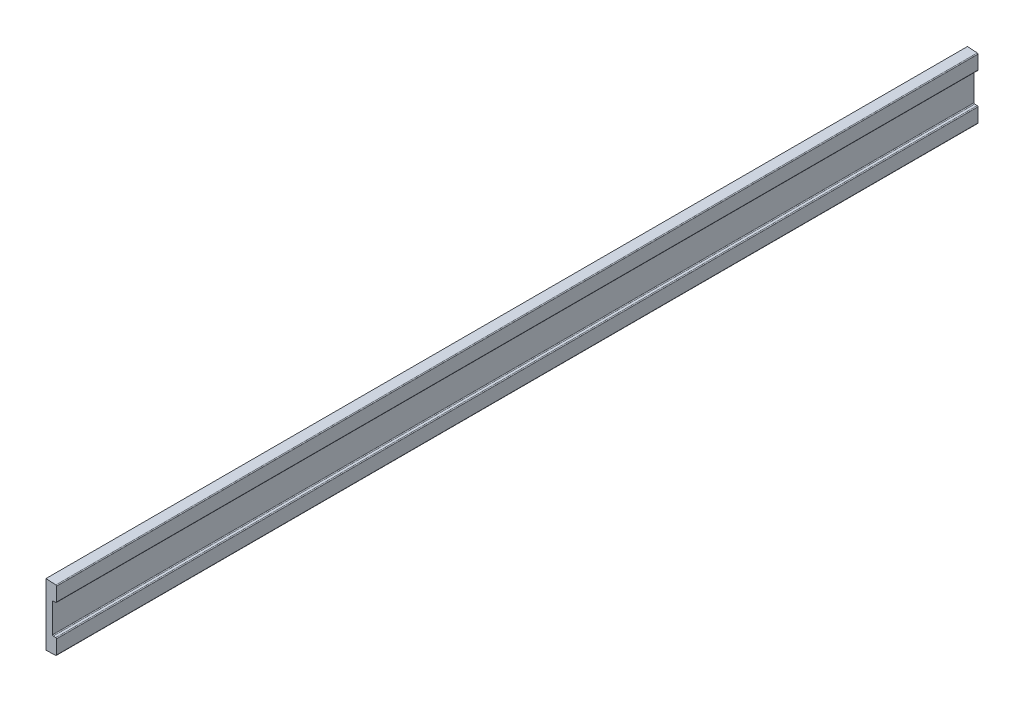
SolidWorks part; units mm, degrees
ref_plane "Front Plane" through (0, 0, 0) normal (0, 0, 1) x (1, 0, 0)
ref_plane "Top Plane" through (0, 0, 0) normal (0, 1, 0) x (1, 0, 0)
ref_plane "Right Plane" through (0, 0, 0) normal (1, 0, 0) x (0, 0, -1)
curve "Curve1"
  spline degree 3 poles (152.4, 0, 0) (152.2328, 0.0185, 0) (151.5718, 0.0917, 0) (150.114, 0.2839, 0) (147.7494, 0.6387, 0) (144.5559, 1.1702, 0) (140.6154, 1.8591, 0) (136.0078, 2.6715, 0) (130.8064, 3.5628, 0) (125.0738, 4.4862, 0) (118.8647, 5.3978, 0) (112.2333, 6.273, 0) (105.2435, 7.1061, 0) (97.9697, 7.8893, 0) (90.4927, 8.6067, 0) (82.8953, 9.2407, 0) (75.2587, 9.7775, 0) (67.6629, 10.1988, 0) (60.1868, 10.4917, 0) (52.9059, 10.6451, 0) (45.8917, 10.6446, 0) (39.2107, 10.4862, 0) (32.9233, 10.1644, 0) (27.0837, 9.6709, 0) (21.7372, 9.0165, 0) (16.9243, 8.2041, 0) (12.6763, 7.2498, 0) (9.0198, 6.1745, 0) (5.9657, 5.002, 0) (3.544, 3.7699, 0) (1.7048, 2.5315, 0) (0.5752, 1.3447, 0) (-0.1707, 0.2031, 0) (0.3376, -1.0018, 0) (1.7929, -1.5467, 0) (3.7942, -2.1772, 0) (6.6434, -2.6439, 0) (10.2161, -3.042, 0) (14.5301, -3.3199, 0) (19.534, -3.4977, 0) (25.1869, -3.5776, 0) (31.4286, -3.5738, 0) (38.1919, -3.4966, 0) (45.4016, -3.3493, 0) (52.9784, -3.1418, 0) (60.8387, -2.8853, 0) (68.895, -2.5879, 0) (77.0574, -2.2589, 0) (85.235, -1.9077, 0) (93.3354, -1.5502, 0) (101.266, -1.1955, 0) (108.9342, -0.8624, 0) (116.2465, -0.5575, 0) (123.1102, -0.3069, 0) (129.4317, -0.1079, 0) (135.1235, 0.028, 0) (140.1036, 0.1089, 0) (144.2994, 0.1399, 0) (147.6448, 0.1242, 0) (150.0834, 0.0865, 0) (151.3998, 0.0403, 0) (151.8986, 0.0229, 0) knots 0 0 0 0 0.001635 0.006466 0.014297 0.024884 0.037944 0.053194 0.070377 0.089257 0.109652 0.131396 0.154295 0.178097 0.202531 0.227329 0.252226 0.276966 0.301297 0.324972 0.347773 0.369494 0.389947 0.408979 0.426466 0.442307 0.456421 0.468774 0.479345 0.488156 0.495223 0.500608 0.504417 0.507344 0.511893 0.518766 0.528062 0.53975 0.553782 0.570059 0.588441 0.608748 0.63075 0.654208 0.678865 0.704451 0.730678 0.757254 0.783883 0.810266 0.836095 0.861073 0.884897 0.907258 0.927856 0.946395 0.962618 0.976286 0.987193 0.995147 1 1 1 1
sketch "Sketch1" plane through (0, 0, 0) normal (0, 0, 1) x (1, 0, 0)
  line L0 (151.8986, 0.0229) -> (152.4, 0)
  line L2 (0, 0) -> (0, 1.9929) construction
  spline S0 degree 3 poles (-13.6531, -1992.4593) (197.8364, 10.3076) (173.4363, -2.7909) (150.114, 0.2839) (147.7494, 0.6387) (144.5559, 1.1702) (140.6154, 1.8591) (136.0078, 2.6715) (130.8064, 3.5628) (125.0738, 4.4862) (118.8647, 5.3978) (112.2333, 6.273) (105.2435, 7.1061) (97.9697, 7.8893) (90.4927, 8.6067) (82.8953, 9.2407) (75.2587, 9.7775) (67.6629, 10.1988) (60.1868, 10.4917) (52.9059, 10.6451) (45.8917, 10.6446) (39.2107, 10.4862) (32.9233, 10.1644) (27.0837, 9.6709) (21.7372, 9.0165) (16.9243, 8.2041) (12.6763, 7.2498) (9.0198, 6.1745) (5.9657, 5.002) (3.544, 3.7699) (1.7048, 2.5315) (0.5752, 1.3447) (-0.1707, 0.2031) (0.3376, -1.0018) (1.7929, -1.5467) (3.7942, -2.1772) (6.6434, -2.6439) (10.2161, -3.042) (14.5301, -3.3199) (19.534, -3.4977) (25.1869, -3.5776) (31.4286, -3.5738) (38.1919, -3.4966) (45.4016, -3.3493) (52.9784, -3.1418) (60.8387, -2.8853) (68.895, -2.5879) (77.0574, -2.2589) (85.235, -1.9077) (93.3354, -1.5502) (101.266, -1.1955) (108.9342, -0.8624) (116.2465, -0.5575) (123.1102, -0.3069) (129.4317, -0.1079) (135.1235, 0.028) (140.1036, 0.1089) (144.2994, 0.1399) (147.6448, 0.1242) (190.703, -0.5421) (231.9179, -27.3192) (328.7943, 1990.768) knots -0.214418 -0.214418 -0.214418 -0.214418 0.001635 0.006466 0.014297 0.024884 0.037944 0.053194 0.070377 0.089257 0.109652 0.131396 0.154295 0.178097 0.202531 0.227329 0.252226 0.276966 0.301297 0.324972 0.347773 0.369494 0.389947 0.408979 0.426466 0.442307 0.456421 0.468774 0.479345 0.488156 0.495223 0.500608 0.504417 0.507344 0.511893 0.518766 0.528062 0.53975 0.553782 0.570059 0.588441 0.608748 0.63075 0.654208 0.678865 0.704451 0.730678 0.757254 0.783883 0.810266 0.836095 0.861073 0.884897 0.907258 0.927856 0.946395 0.962618 0.976286 0.987193 0.995147 1.394988 1.394988 1.394988 1.394988 only from (152.4, 0) to (151.8986, 0.0229) construction
  spline S1 degree 3 poles (152.4, 0) (152.2328, 0.0185) (151.5718, 0.0917) (150.114, 0.2839) (147.7494, 0.6387) (144.5559, 1.1702) (140.6154, 1.8591) (136.0078, 2.6715) (130.8064, 3.5628) (125.0738, 4.4862) (118.8647, 5.3978) (112.2333, 6.273) (105.2435, 7.1061) (97.9697, 7.8893) (90.4927, 8.6067) (82.8953, 9.2407) (75.2587, 9.7775) (67.6629, 10.1988) (60.1868, 10.4917) (52.9059, 10.6451) (45.8917, 10.6446) (39.2107, 10.4862) (32.9233, 10.1644) (27.0837, 9.6709) (21.7372, 9.0165) (16.9243, 8.2041) (12.6763, 7.2498) (9.0198, 6.1745) (5.9657, 5.002) (3.544, 3.7699) (1.7048, 2.5315) (0.5752, 1.3447) (-0.1707, 0.2031) (0.3376, -1.0018) (1.7929, -1.5467) (3.7942, -2.1772) (6.6434, -2.6439) (10.2161, -3.042) (14.5301, -3.3199) (19.534, -3.4977) (25.1869, -3.5776) (31.4286, -3.5738) (38.1919, -3.4966) (45.4016, -3.3493) (52.9784, -3.1418) (60.8387, -2.8853) (68.895, -2.5879) (77.0574, -2.2589) (85.235, -1.9077) (93.3354, -1.5502) (101.266, -1.1955) (108.9342, -0.8624) (116.2465, -0.5575) (123.1102, -0.3069) (129.4317, -0.1079) (135.1235, 0.028) (140.1036, 0.1089) (144.2994, 0.1399) (147.6448, 0.1242) (150.0834, 0.0865) (151.3998, 0.0403) (151.8986, 0.0229) knots 0 0 0 0 0.001635 0.006466 0.014297 0.024884 0.037944 0.053194 0.070377 0.089257 0.109652 0.131396 0.154295 0.178097 0.202531 0.227329 0.252226 0.276966 0.301297 0.324972 0.347773 0.369494 0.389947 0.408979 0.426466 0.442307 0.456421 0.468774 0.479345 0.488156 0.495223 0.500608 0.504417 0.507344 0.511893 0.518766 0.528062 0.53975 0.553782 0.570059 0.588441 0.608748 0.63075 0.654208 0.678865 0.704451 0.730678 0.757254 0.783883 0.810266 0.836095 0.861073 0.884897 0.907258 0.927856 0.946395 0.962618 0.976286 0.987193 0.995147 1 1 1 1
extrude "Boss-Extrude1" add sketch "Sketch1" along normal blind 177.8
sketch "Sketch3" plane through (0, 0, 177.8) normal (0, 0, 1) x (1, 0, 0)
  line L0 (76.2, 9.6986) -> (76.2, -2.2909)
  line L1 (0, 0) -> (0, 3.7038) construction
  line L2 (76.2, 3.7038) -> (0, 3.7038) construction
  line L3 (78.232, 9.6986) -> (78.232, -2.2909)
  line L4 (151.8986, 0.0229) -> (152.4, 0)
  line L5 (151.8986, 0.0229) -> (152.4, 0)
  line L6 (78.232, 0.7701) -> (78.232, 6.6375)
  line L7 (78.232, 3.7038) -> (76.2, 3.7038) construction
  line L8 (77.4446, 6.6375) -> (77.4446, 0.7701)
  line L9 (78.232, 6.6375) -> (77.4446, 6.6375)
  line L10 (78.232, 0.7701) -> (77.4446, 0.7701)
  spline S0 degree 3 poles (152.4, 0) (152.2328, 0.0185) (151.5718, 0.0917) (150.114, 0.2839) (147.7494, 0.6387) (144.5559, 1.1702) (140.6154, 1.8591) (136.0078, 2.6715) (130.8064, 3.5628) (125.0738, 4.4862) (118.8647, 5.3978) (112.2333, 6.273) (105.2435, 7.1061) (97.9697, 7.8893) (90.4927, 8.6067) (82.8953, 9.2407) (75.2587, 9.7775) (67.6629, 10.1988) (60.1868, 10.4917) (52.9059, 10.6451) (45.8917, 10.6446) (39.2107, 10.4862) (32.9233, 10.1644) (27.0837, 9.6709) (21.7372, 9.0165) (16.9243, 8.2041) (12.6763, 7.2498) (9.0198, 6.1745) (5.9657, 5.002) (3.544, 3.7699) (1.7048, 2.5315) (0.5752, 1.3447) (-0.1707, 0.2031) (0.3376, -1.0018) (1.7929, -1.5467) (3.7942, -2.1772) (6.6434, -2.6439) (10.2161, -3.042) (14.5301, -3.3199) (19.534, -3.4977) (25.1869, -3.5776) (31.4286, -3.5738) (38.1919, -3.4966) (45.4016, -3.3493) (52.9784, -3.1418) (60.8387, -2.8853) (68.895, -2.5879) (77.0574, -2.2589) (85.235, -1.9077) (93.3354, -1.5502) (101.266, -1.1955) (108.9342, -0.8624) (116.2465, -0.5575) (123.1102, -0.3069) (129.4317, -0.1079) (135.1235, 0.028) (140.1036, 0.1089) (144.2994, 0.1399) (147.6448, 0.1242) (150.0834, 0.0865) (151.3998, 0.0403) (151.8986, 0.0229) knots 0 0 0 0 0.001635 0.006466 0.014297 0.024884 0.037944 0.053194 0.070377 0.089257 0.109652 0.131396 0.154295 0.178097 0.202531 0.227329 0.252226 0.276966 0.301297 0.324972 0.347773 0.369494 0.389947 0.408979 0.426466 0.442307 0.456421 0.468774 0.479345 0.488156 0.495223 0.500608 0.504417 0.507344 0.511893 0.518766 0.528062 0.53975 0.553782 0.570059 0.588441 0.608748 0.63075 0.654208 0.678865 0.704451 0.730678 0.757254 0.783883 0.810266 0.836095 0.861073 0.884897 0.907258 0.927856 0.946395 0.962618 0.976286 0.987193 0.995147 1 1 1 1 construction
  spline S1 degree 3 poles (152.4, 0) (152.2328, 0.0185) (151.5718, 0.0917) (150.114, 0.2839) (147.7494, 0.6387) (144.5559, 1.1702) (140.6154, 1.8591) (136.0078, 2.6715) (130.8064, 3.5628) (125.0738, 4.4862) (118.8647, 5.3978) (112.2333, 6.273) (105.2435, 7.1061) (97.9697, 7.8893) (90.4927, 8.6067) (82.8953, 9.2407) (75.2587, 9.7775) (67.6629, 10.1988) (60.1868, 10.4917) (52.9059, 10.6451) (45.8917, 10.6446) (39.2107, 10.4862) (32.9233, 10.1644) (27.0837, 9.6709) (21.7372, 9.0165) (16.9243, 8.2041) (12.6763, 7.2498) (9.0198, 6.1745) (5.9657, 5.002) (3.544, 3.7699) (1.7048, 2.5315) (0.5752, 1.3447) (-0.1707, 0.2031) (0.3376, -1.0018) (1.7929, -1.5467) (3.7942, -2.1772) (6.6434, -2.6439) (10.2161, -3.042) (14.5301, -3.3199) (19.534, -3.4977) (25.1869, -3.5776) (31.4286, -3.5738) (38.1919, -3.4966) (45.4016, -3.3493) (52.9784, -3.1418) (60.8387, -2.8853) (68.895, -2.5879) (77.0574, -2.2589) (85.235, -1.9077) (93.3354, -1.5502) (101.266, -1.1955) (108.9342, -0.8624) (116.2465, -0.5575) (123.1102, -0.3069) (129.4317, -0.1079) (135.1235, 0.028) (140.1036, 0.1089) (144.2994, 0.1399) (147.6448, 0.1242) (150.0834, 0.0865) (151.3998, 0.0403) (151.8986, 0.0229) knots 0 0 0 0 0.001635 0.006466 0.014297 0.024884 0.037944 0.053194 0.070377 0.089257 0.109652 0.131396 0.154295 0.178097 0.202531 0.227329 0.252226 0.276966 0.301297 0.324972 0.347773 0.369494 0.389947 0.408979 0.426466 0.442307 0.456421 0.468774 0.479345 0.488156 0.495223 0.500608 0.504417 0.507344 0.511893 0.518766 0.528062 0.53975 0.553782 0.570059 0.588441 0.608748 0.63075 0.654208 0.678865 0.704451 0.730678 0.757254 0.783883 0.810266 0.836095 0.861073 0.884897 0.907258 0.927856 0.946395 0.962618 0.976286 0.987193 0.995147 1 1 1 1 construction
  spline S3 degree 3 poles (-559.3612, -6961.6106) (222.8724, 27.5623) (184.7724, -4.2854) (150.114, 0.2839) (147.7494, 0.6387) (144.5559, 1.1702) (140.6154, 1.8591) (136.0078, 2.6715) (130.8064, 3.5628) (125.0738, 4.4862) (118.8647, 5.3978) (112.2333, 6.273) (105.2435, 7.1061) (97.9697, 7.8893) (90.4927, 8.6067) (82.8953, 9.2407) (75.2587, 9.7775) (67.6629, 10.1988) (60.1868, 10.4917) (52.9059, 10.6451) (45.8917, 10.6446) (39.2107, 10.4862) (32.9233, 10.1644) (27.0837, 9.6709) (21.7372, 9.0165) (16.9243, 8.2041) (12.6763, 7.2498) (9.0198, 6.1745) (5.9657, 5.002) (3.544, 3.7699) (1.7048, 2.5315) (0.5752, 1.3447) (-0.1707, 0.2031) (0.3376, -1.0018) (1.7929, -1.5467) (3.7942, -2.1772) (6.6434, -2.6439) (10.2161, -3.042) (14.5301, -3.3199) (19.534, -3.4977) (25.1869, -3.5776) (31.4286, -3.5738) (38.1919, -3.4966) (45.4016, -3.3493) (52.9784, -3.1418) (60.8387, -2.8853) (68.895, -2.5879) (77.0574, -2.2589) (85.235, -1.9077) (93.3354, -1.5502) (101.266, -1.1955) (108.9342, -0.8624) (116.2465, -0.5575) (123.1102, -0.3069) (129.4317, -0.1079) (135.1235, 0.028) (140.1036, 0.1089) (144.2994, 0.1399) (147.6448, 0.1242) (211.7851, -0.8684) (273.1741, -60.8447) (530.0376, 6986.0071) knots -0.325587 -0.325587 -0.325587 -0.325587 0.001635 0.006466 0.014297 0.024884 0.037944 0.053194 0.070377 0.089257 0.109652 0.131396 0.154295 0.178097 0.202531 0.227329 0.252226 0.276966 0.301297 0.324972 0.347773 0.369494 0.389947 0.408979 0.426466 0.442307 0.456421 0.468774 0.479345 0.488156 0.495223 0.500608 0.504417 0.507344 0.511893 0.518766 0.528062 0.53975 0.553782 0.570059 0.588441 0.608748 0.63075 0.654208 0.678865 0.704451 0.730678 0.757254 0.783883 0.810266 0.836095 0.861073 0.884897 0.907258 0.927856 0.946395 0.962618 0.976286 0.987193 0.995147 1.599992 1.599992 1.599992 1.599992 only from (152.4, 0) to (151.8986, 0.0229)
  spline S5 degree 3 poles (152.4, 0) (152.2328, 0.0185) (151.5718, 0.0917) (150.114, 0.2839) (147.7494, 0.6387) (144.5559, 1.1702) (140.6154, 1.8591) (136.0078, 2.6715) (130.8064, 3.5628) (125.0738, 4.4862) (118.8647, 5.3978) (112.2333, 6.273) (105.2435, 7.1061) (97.9697, 7.8893) (90.4927, 8.6067) (82.8953, 9.2407) (75.2587, 9.7775) (67.6629, 10.1988) (60.1868, 10.4917) (52.9059, 10.6451) (45.8917, 10.6446) (39.2107, 10.4862) (32.9233, 10.1644) (27.0837, 9.6709) (21.7372, 9.0165) (16.9243, 8.2041) (12.6763, 7.2498) (9.0198, 6.1745) (5.9657, 5.002) (3.544, 3.7699) (1.7048, 2.5315) (0.5752, 1.3447) (-0.1707, 0.2031) (0.3376, -1.0018) (1.7929, -1.5467) (3.7942, -2.1772) (6.6434, -2.6439) (10.2161, -3.042) (14.5301, -3.3199) (19.534, -3.4977) (25.1869, -3.5776) (31.4286, -3.5738) (38.1919, -3.4966) (45.4016, -3.3493) (52.9784, -3.1418) (60.8387, -2.8853) (68.895, -2.5879) (77.0574, -2.2589) (85.235, -1.9077) (93.3354, -1.5502) (101.266, -1.1955) (108.9342, -0.8624) (116.2465, -0.5575) (123.1102, -0.3069) (129.4317, -0.1079) (135.1235, 0.028) (140.1036, 0.1089) (144.2994, 0.1399) (147.6448, 0.1242) (150.0834, 0.0865) (151.3998, 0.0403) (151.8986, 0.0229) knots 0 0 0 0 0.001635 0.006466 0.014297 0.024884 0.037944 0.053194 0.070377 0.089257 0.109652 0.131396 0.154295 0.178097 0.202531 0.227329 0.252226 0.276966 0.301297 0.324972 0.347773 0.369494 0.389947 0.408979 0.426466 0.442307 0.456421 0.468774 0.479345 0.488156 0.495223 0.500608 0.504417 0.507344 0.511893 0.518766 0.528062 0.53975 0.553782 0.570059 0.588441 0.608748 0.63075 0.654208 0.678865 0.704451 0.730678 0.757254 0.783883 0.810266 0.836095 0.861073 0.884897 0.907258 0.927856 0.946395 0.962618 0.976286 0.987193 0.995147 1 1 1 1
  point P18 (78.232, 3.7038)
  point P22 (77.4446, 3.7038)
  spline M6 degree 3 poles (152.4, 0) (152.2328, 0.0185) (151.5718, 0.0917) (150.114, 0.2839) (147.7494, 0.6387) (144.5559, 1.1702) (140.6154, 1.8591) (136.0078, 2.6715) (130.8064, 3.5628) (125.0738, 4.4862) (118.8647, 5.3978) (112.2333, 6.273) (105.2435, 7.1061) (97.9697, 7.8893) (90.4927, 8.6067) (82.8953, 9.2407) (75.2587, 9.7775) (67.6629, 10.1988) (60.1868, 10.4917) (52.9059, 10.6451) (45.8917, 10.6446) (39.2107, 10.4862) (32.9233, 10.1644) (27.0837, 9.6709) (21.7372, 9.0165) (16.9243, 8.2041) (12.6763, 7.2498) (9.0198, 6.1745) (5.9657, 5.002) (3.544, 3.7699) (1.7048, 2.5315) (0.5752, 1.3447) (-0.1707, 0.2031) (0.3376, -1.0018) (1.7929, -1.5467) (3.7942, -2.1772) (6.6434, -2.6439) (10.2161, -3.042) (14.5301, -3.3199) (19.534, -3.4977) (25.1869, -3.5776) (31.4286, -3.5738) (38.1919, -3.4966) (45.4016, -3.3493) (52.9784, -3.1418) (60.8387, -2.8853) (68.895, -2.5879) (77.0574, -2.2589) (85.235, -1.9077) (93.3354, -1.5502) (101.266, -1.1955) (108.9342, -0.8624) (116.2465, -0.5575) (123.1102, -0.3069) (129.4317, -0.1079) (135.1235, 0.028) (140.1036, 0.1089) (144.2994, 0.1399) (147.6448, 0.1242) (150.0834, 0.0865) (151.3998, 0.0403) (151.8986, 0.0229) knots 0 0 0 0 0.001635 0.006466 0.014297 0.024884 0.037944 0.053194 0.070377 0.089257 0.109652 0.131396 0.154295 0.178097 0.202531 0.227329 0.252226 0.276966 0.301297 0.324972 0.347773 0.369494 0.389947 0.408979 0.426466 0.442307 0.456421 0.468774 0.479345 0.488156 0.495223 0.500608 0.504417 0.507344 0.511893 0.518766 0.528062 0.53975 0.553782 0.570059 0.588441 0.608748 0.63075 0.654208 0.678865 0.704451 0.730678 0.757254 0.783883 0.810266 0.836095 0.861073 0.884897 0.907258 0.927856 0.946395 0.962618 0.976286 0.987193 0.995147 1 1 1 1
  line M12 (151.8986, 0.0229) -> (152.4, 0)
  dimension "D2" = 76.2
  dimension "D4" = 0.7874
  dimension "D5" = 5.8674
  dimension "D1" = 0
  dimension "D3" = 2.032
extrude "Cut-Extrude1" cut sketch "Sketch3" against normal up to next contours L0 M6 | L3 M6 M12 | L10 L8 L9 L6
fillet "Fillet1" radius 0.1588 6 edges at (78.232, 0.7701, 88.9) (77.4446, 0.7701, 88.9) (78.232, 6.6375, 88.9) (77.4446, 6.6375, 88.9)
